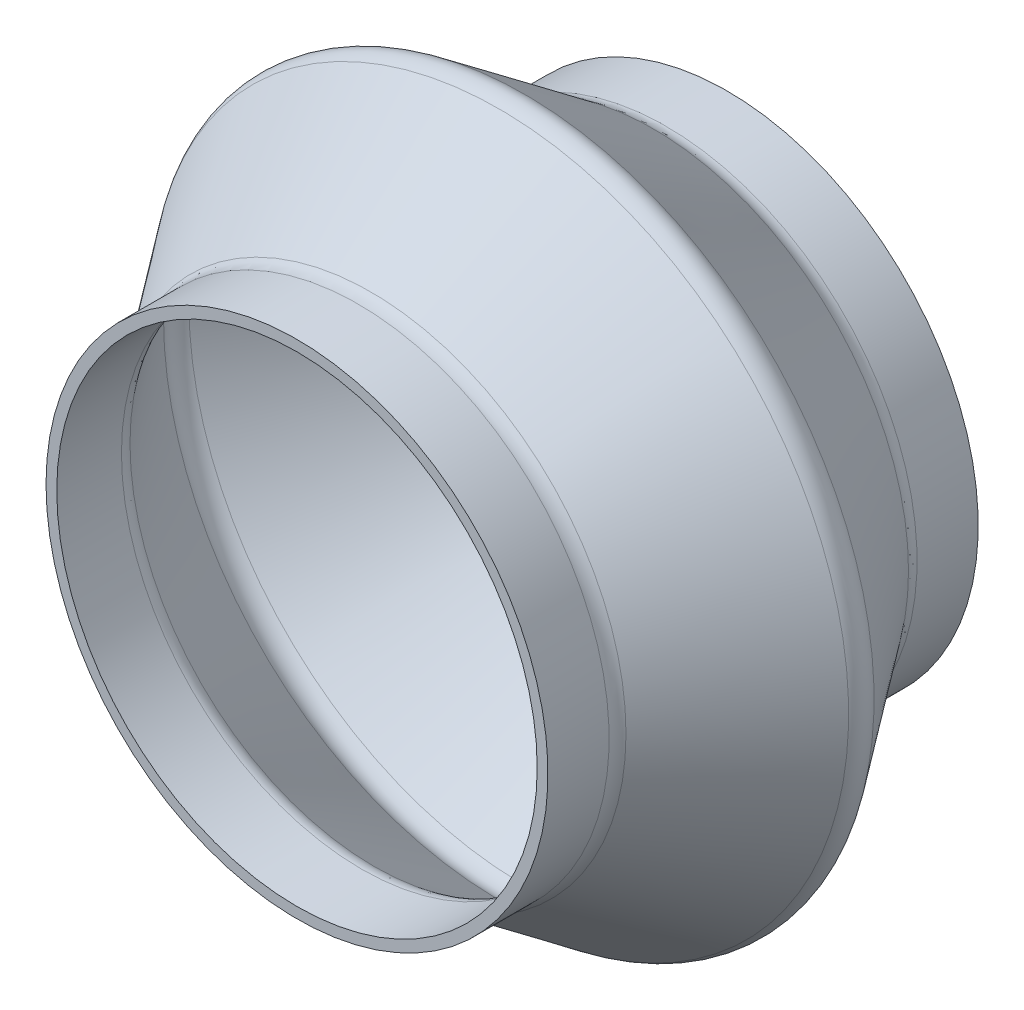
SolidWorks part; units mm, degrees
ref_plane "Front Plane" through (0, 0, 0) normal (0, 0, 1) x (1, 0, 0)
ref_plane "Top Plane" through (0, 0, 0) normal (0, 1, 0) x (1, 0, 0)
ref_plane "Right Plane" through (0, 0, 0) normal (1, 0, 0) x (0, 0, -1)
sketch "Sketch1" plane through (0, 0, 0) normal (0, 1, 0) x (1, 0, 0)
  line L0 (0, 72.547) -> (0, -16.6481) construction
  line L1 (-39.0431, 0) -> (62.4183, 0) construction
  line L2 (-35, 0) -> (-35, 8.5289)
  line L3 (-35.5793, 10.301) -> (-48.7028, 28.2279)
  line L4 (-48.7028, 31.7721) -> (-35.5793, 49.699)
  line L5 (-35, 51.4711) -> (-35, 60)
  line L6 (-35, 60) -> (-33.5, 60)
  line L7 (-33.5, 60) -> (-33.5, 50.9807)
  line L8 (-34.0793, 49.2087) -> (-46.8438, 31.7721)
  line L9 (-46.8438, 28.2279) -> (-34.0793, 10.7913)
  line L10 (-33.5, 9.0193) -> (-33.5, 0)
  line L11 (-33.5, 0) -> (-35, 0)
  arc A0 (-35, 8.5289) -> (-35.5793, 10.301) centre (-38, 8.5289) ccw
  arc A1 (-34.0793, 10.7913) -> (-33.5, 9.0193) centre (-36.5, 9.0193) cw
  arc A2 (-33.5, 50.9807) -> (-34.0793, 49.2087) centre (-36.5, 50.9807) cw
  arc A3 (-35.5793, 49.699) -> (-35, 51.4711) centre (-38, 51.4711) ccw
  arc A4 (-48.7028, 28.2279) -> (-48.7028, 31.7721) centre (-46.2821, 30) cw
  arc A5 (-46.8438, 31.7721) -> (-46.8438, 28.2279) centre (-44.4231, 30) ccw
  point P15 (-39.0431, 0)
  point P16 (0, 0)
  point P17 (-34.25, 60)
  point P18 (-35.4871, 57.905)
  point P19 (0, 72.547)
  point P20 (0, 0)
  point P22 (-35.7393, 38.2305)
  point P26 (-33.5, 10)
  point P29 (-33.5, 50)
  point P34 (-50, 30)
  dimension "D12" = 3
  dimension "D1" = 1.5
  dimension "D2" = 33.5
  dimension "D3" = 10
  dimension "D4" = 60
  dimension "D5" = 10
  dimension "D6" = 1.5
  dimension "D7" = 33.5
  dimension "D8" = 1.5
  dimension "D9" = 1.5
  dimension "D10" = 50
  dimension "D11" = 30
revolve "Revolve1" add sketch "Sketch1" angle 360 about L0
